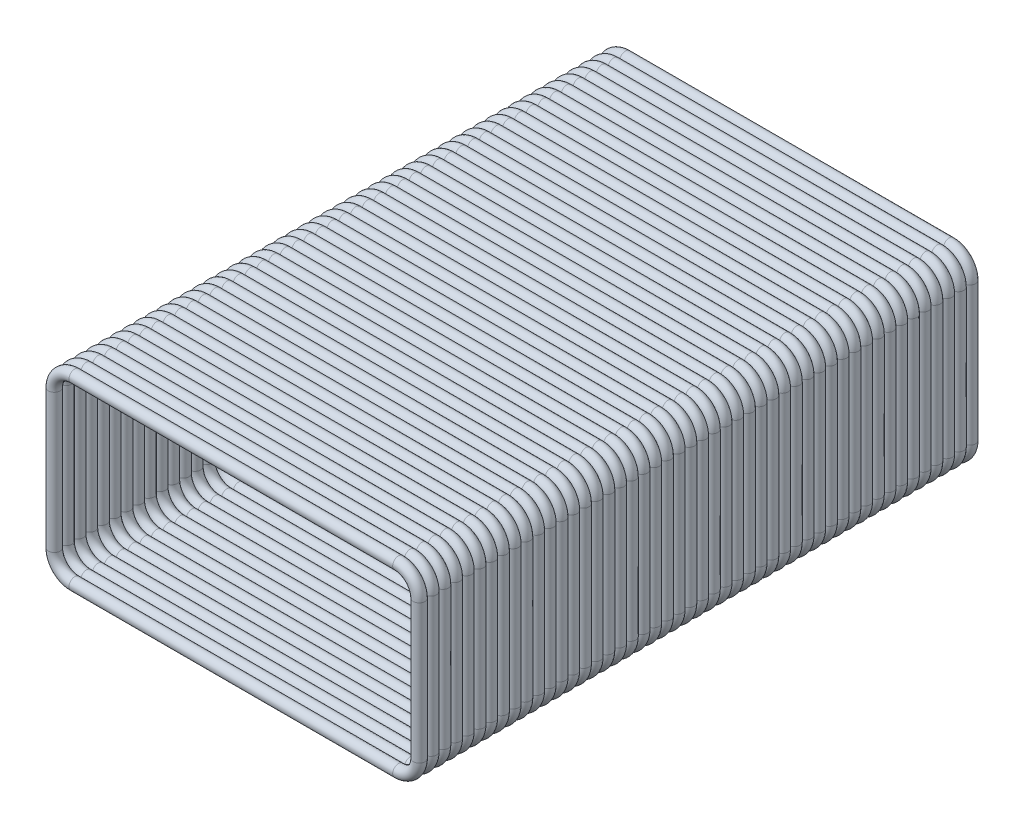
SolidWorks part; units mm, degrees
ref_plane "Front Plane" through (0, 0, 0) normal (0, 0, 1) x (1, 0, 0)
ref_plane "Top Plane" through (0, 0, 0) normal (0, 1, 0) x (1, 0, 0)
ref_plane "Right Plane" through (0, 0, 0) normal (1, 0, 0) x (0, 0, -1)
sketch "Sketch1" plane through (0, 0, 0) normal (0, 0, 1) x (1, 0, 0)
  line L1 (-15.75, -8.75) -> (15.75, -8.75)
  line L2 (-17.75, -6.75) -> (-17.75, 6.75)
  line L3 (-15.75, 8.75) -> (15.75, 8.75)
  line L4 (17.75, -6.75) -> (17.75, 6.75)
  line L5 (-17.75, -8.75) -> (17.75, 8.75) construction
  line L6 (-17.75, 8.75) -> (17.75, -8.75) construction
  arc A0 (-17.75, 6.75) -> (-15.75, 8.75) centre (-15.75, 6.75) cw
  arc A1 (15.75, 8.75) -> (17.75, 6.75) centre (15.75, 6.75) cw
  arc A2 (15.75, -8.75) -> (17.75, -6.75) centre (15.75, -6.75) ccw
  arc A3 (-15.75, -8.75) -> (-17.75, -6.75) centre (-15.75, -6.75) cw
  point P0 (0, 0)
  dimension "D3" = 2
  dimension "D1" = 17.5
  dimension "D2" = 35.5
sweep "Sweep1" add path "Sketch1" circular profile diameter 1.14 parameters "D3"=1.14
sketch "Sketch14" plane through (0, 0, 0) normal (0, 1, 0) x (1, 0, 0)
  line L0 (0, 0) -> (0, -55)
  dimension "D1" = 55
pattern_linear "LPattern1" count 48 spacing 1.14 along (0, 0, 1) of "Sweep1"
